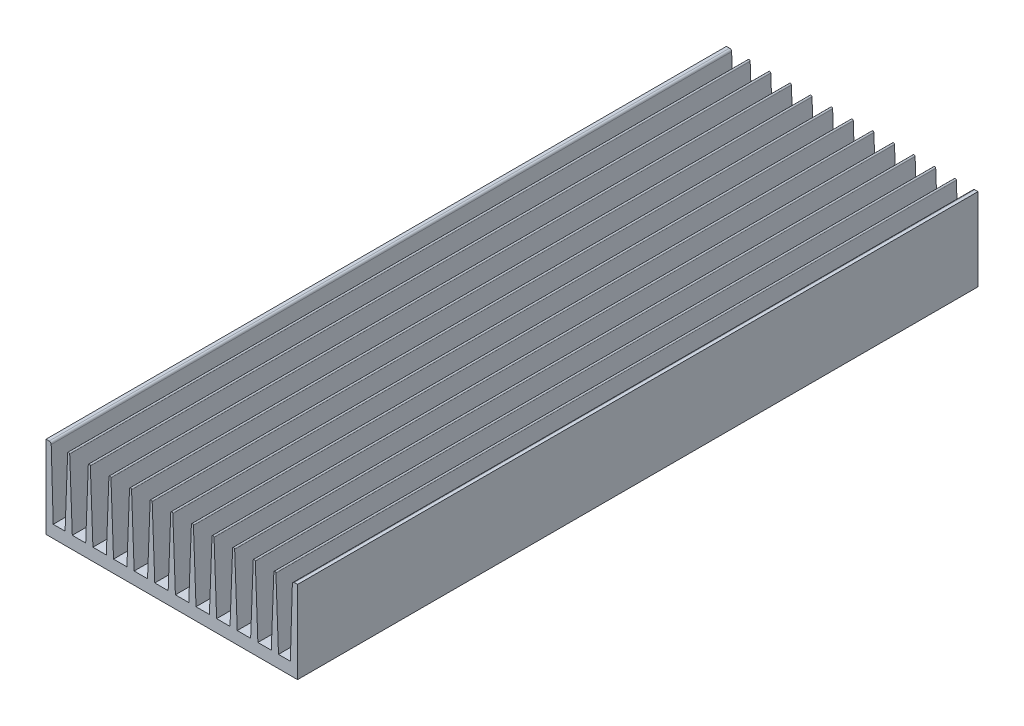
SolidWorks part; units mm, degrees
ref_plane "Спереди" through (0, 0, 0) normal (0, 0, 1) x (1, 0, 0)
ref_plane "Сверху" through (0, 0, 0) normal (0, 1, 0) x (1, 0, 0)
ref_plane "Справа" through (0, 0, 0) normal (1, 0, 0) x (0, 0, -1)
sketch "Эскиз1" plane through (0, 0, 0) normal (0, 0, 1) x (1, 0, 0)
  line L0 (0, 40) -> (1.529, 40)
  line L1 (0, 0) -> (122, 0)
  line L2 (2.5285, 39.0294) -> (3.5, 6)
  line L3 (0, 40) -> (0, 0)
  line L4 (122, 40) -> (122, 0)
  line L5 (61, 63.7127) -> (61, -22.2582) construction
  line L8 (122, 40) -> (120.471, 40)
  line L9 (119.4715, 39.0294) -> (118.5, 6)
  line L10 (3.5, 6) -> (118.5, 6)
  arc A0 (1.529, 40) -> (2.5285, 39.0294) centre (1.529, 39) cw
  arc A2 (120.471, 40) -> (119.4715, 39.0294) centre (120.471, 39) ccw
  point P18 (119.5, 40)
  dimension "D9" = 1
  dimension "D1" = 122
  dimension "D2" = 6
  dimension "D3" = 40
  dimension "D4" = 3.5
  dimension "D7" = 2.5
extrude "Вытянуть1" add sketch "Эскиз1" along normal blind 330
sketch "Эскиз2" plane through (0, 0, 330) normal (0, 0, 1) x (1, 0, 0)
  line L0 (118.5, 6) -> (3.5, 6) construction
  line L1 (10.5, 39.5) -> (9.25, 6)
  line L2 (11, 39.5) -> (11, 22.5548) construction
  line L3 (11.5, 39.5) -> (12.75, 6)
  line L4 (9.25, 6) -> (12.75, 6)
  line L6 (0, 40) -> (0, 0) construction
  arc A0 (10.5, 39.5) -> (11.5, 39.5) centre (11, 39.5) cw
  dimension "D1" = 34
  dimension "D3" = 0.5
  dimension "D2" = 3.5
  dimension "D4" = 11
  dimension "D5" = 1
extrude "Вытянуть3" add sketch "Эскиз2" against normal blind 330
pattern_curve "Кривая1" of "Вытянуть3" along edge at (61, 0, 0) parameters "D1"=11, "D3"=10, "D2"=1, "D4"=50
sketch "Эскиз3" plane through (0, 0, 0) normal (0, -1, 0) x (1, 0, 0)
  line L0 (-14.0506, 322) -> (137.5079, 322) construction
  line L1 (0, 330) -> (122, 330) construction
  line L2 (0, 330) -> (0, 0) construction
  line L3 (-46.7511, 165) -> (151.4312, 165) construction
  line L4 (0, 0) -> (122, 0) construction
  circle A0 centre (26, 322) radius 2.25
  circle A1 centre (96, 322) radius 2.25
  circle A2 centre (96, 8) radius 2.25
  circle A3 centre (26, 8) radius 2.25
  dimension "D2" = 70
  dimension "D4" = 4.5
  dimension "D1" = 8
  dimension "D3" = 26
extrude "Вырез-Вытянуть1" cut sketch "Эскиз3" against normal blind 6
sketch "Эскиз4" plane through (1.488, 0, 27.4005) normal (0, -1, 0) x (1, 0, 0)
  line L0 (60.512, 141.5995) -> (60.512, 276.5995) construction
  line L2 (120.512, 302.5995) -> (120.512, -27.4005) construction
  line L3 (-1.488, 302.5995) -> (120.512, 302.5995) construction
  line L4 (65.512, -13.2049) -> (65.512, 92.5037) construction
  line L5 (-1.488, 302.5995) -> (-1.488, -27.4005) construction
  line L6 (-1.488, -27.4005) -> (120.512, -27.4005) construction
  circle A1 centre (65.512, 131.5995) radius 1.6
  circle A2 centre (103.512, 188.9995) radius 1.6
  circle A3 centre (60.512, 276.5995) radius 1.6
  circle A4 centre (60.512, 141.5995) radius 1.6
  circle A5 centre (65.512, -3.4005) radius 1.6
  circle A6 centre (38.512, 113.5995) radius 2.1
  circle A7 centre (109.632, 2.9195) radius 2.5
  circle A8 centre (28.012, 76.0995) radius 1.6
  circle A9 centre (48.712, 22.9295) radius 1.1
  dimension "D2" = 3.2
  dimension "D4" = 43
  dimension "D5" = 60
  dimension "D7" = 135
  dimension "D8" = 3.2
  dimension "D9" = 50.2
  dimension "D1" = 26
  dimension "D10" = 50.33
  dimension "D11" = 135
  dimension "D6" = 55
  dimension "D12" = 29.5
  dimension "D13" = 3.2
  dimension "D14" = 4.2
  dimension "D19" = 5
  dimension "D20" = 30.32
  dimension "D21" = 10.88
  dimension "D22" = 2.2
  dimension "D3" = 47.4
  dimension "D18" = 103.5
  dimension "D15" = 40
  dimension "D16" = 141
  dimension "D17" = 24
extrude "Вырез-Вытянуть2" cut sketch "Эскиз4" against normal blind 6
cosmetic thread "Условное изображение резьбы6" parameters "D2"=4
cosmetic thread "Условное изображение резьбы8" parameters "D2"=4
cosmetic thread "Условное изображение резьбы9" parameters "D1"=6, "D2"=4
cosmetic thread "Условное изображение резьбы10" parameters "D1"=6, "D2"=4
cosmetic thread "Условное изображение резьбы11" parameters "D1"=6, "D2"=5
cosmetic thread "Условное изображение резьбы13" parameters "D1"=6, "D2"=4
cosmetic thread "Условное изображение резьбы15" parameters "D1"=6, "D2"=3
cosmetic thread "Условное изображение резьбы16" parameters "D1"=5, "D2"=4
